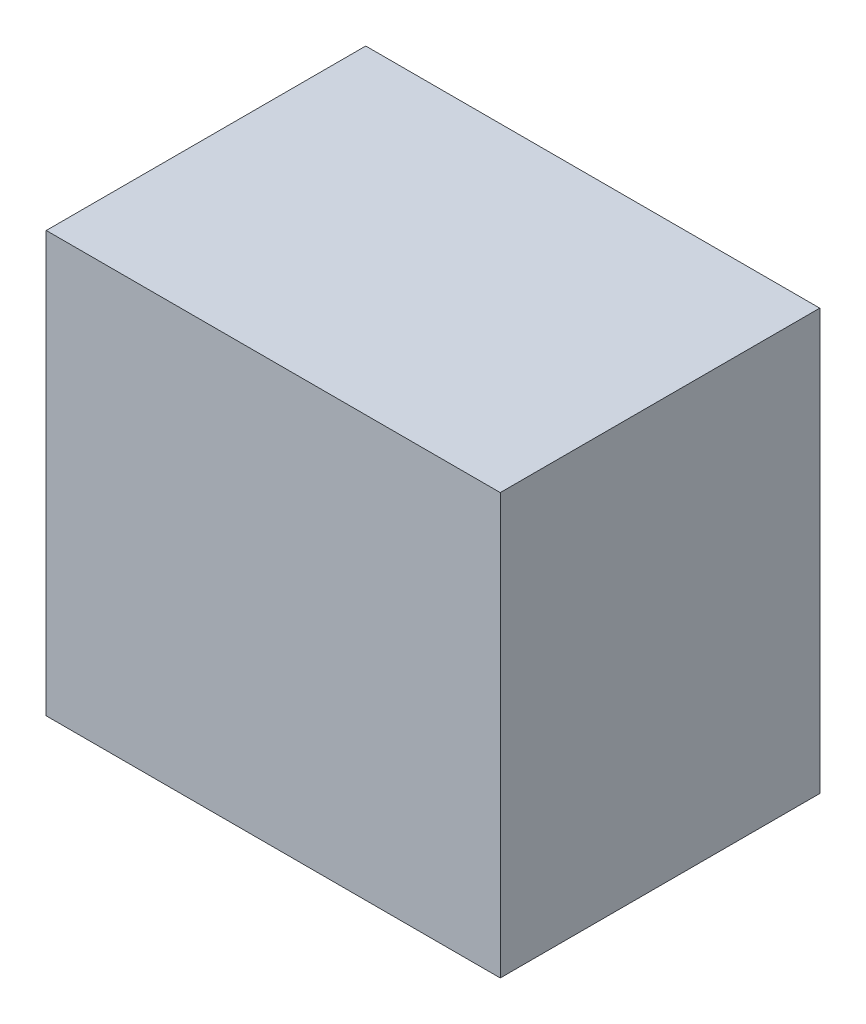
SolidWorks part; units mm, degrees
ref_plane "Спереди" through (0, 0, 0) normal (0, 0, 1) x (1, 0, 0)
ref_plane "Сверху" through (0, 0, 0) normal (0, 1, 0) x (1, 0, 0)
ref_plane "Справа" through (0, 0, 0) normal (1, 0, 0) x (0, 0, -1)
sketch "Эскиз1" plane through (0, 0, 0) normal (0, 1, 0) x (1, 0, 0)
  line L1 (0, 0) -> (5.4, 0)
  line L2 (0, 0) -> (0, 3.8)
  line L3 (0, 3.8) -> (5.4, 3.8)
  line L4 (5.4, 0) -> (5.4, 3.8)
  dimension "D1" = 3.8
  dimension "D2" = 5.4
extrude "Бобышка-Вытянуть1" add sketch "Эскиз1" along normal blind 5
